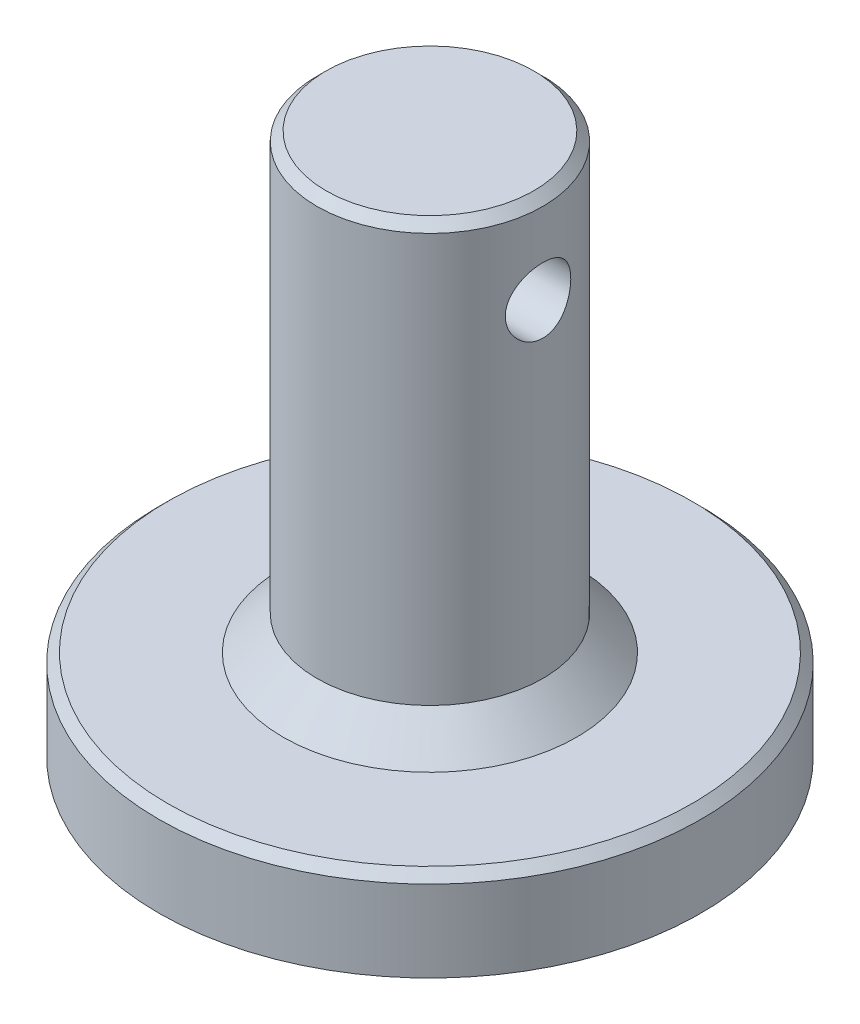
SolidWorks part; units mm, degrees
ref_plane "前视基准面" through (0, 0, 0) normal (0, 0, 1) x (1, 0, 0)
ref_plane "上视基准面" through (0, 0, 0) normal (0, 1, 0) x (1, 0, 0)
ref_plane "右视基准面" through (0, 0, 0) normal (1, 0, 0) x (0, 0, -1)
other "Configuration Table"
sketch "草图1" plane through (0, 0, 0) normal (0, 1, 0) x (1, 0, 0)
  circle A0 centre (0, 0) radius 12
  dimension "D1" = 24
extrude "凸台-拉伸1" add sketch "草图1" along normal blind 4
sketch "草图2" plane through (0, 4, 0) normal (0, 1, 0) x (1, 0, 0)
  circle A0 centre (0, 0) radius 5
  dimension "D1" = 10
extrude "凸台-拉伸2" add sketch "草图2" along normal blind 20
chamfer "倒角1" distance 0.4 angle 45 2 edges at (0, 4, 12) (0, 24, 5)
sketch "草图4" plane through (0, 0, 0) normal (1, 0, 0) x (0, 0, -1)
  line L0 (4.6, 24) -> (-4.6, 24) construction
  circle A0 centre (0, 20) radius 1.45
  dimension "D1" = 4
  dimension "D2" = 2.9
extrude "切除-拉伸1" cut sketch "草图4" along normal through all and the other way through all
chamfer "倒角2" distance 1.5 angle 45 1 edges at (0, 4, 5)
